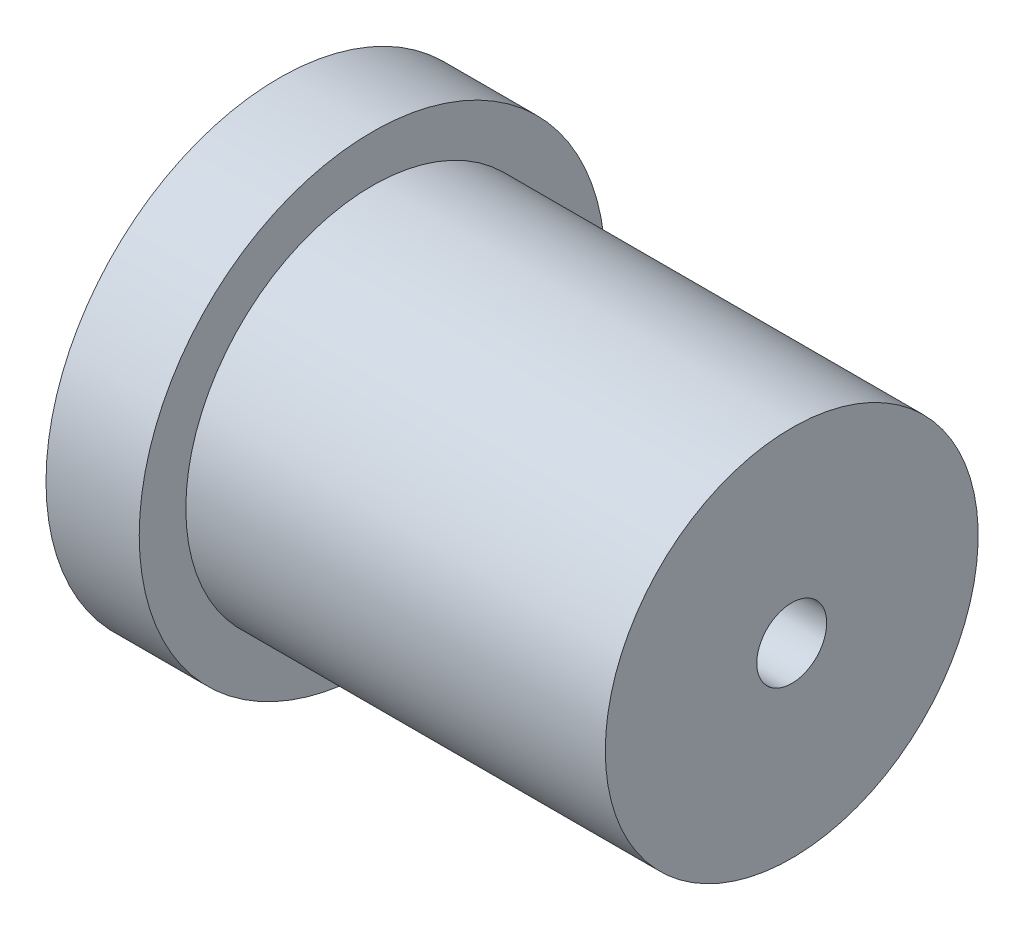
SolidWorks part; units mm, degrees
ref_plane "Front Plane" through (0, 0, 0) normal (0, 0, 1) x (1, 0, 0)
ref_plane "Top Plane" through (0, 0, 0) normal (0, 1, 0) x (1, 0, 0)
ref_plane "Right Plane" through (0, 0, 0) normal (1, 0, 0) x (0, 0, -1)
sketch "Sketch1" plane through (0, 0, 0) normal (0, 0, 1) x (1, 0, 0)
  line L0 (-2.75, 2.5) -> (-1.75, 2.5)
  line L1 (-2.75, 2.5) -> (2.75, 2.5) construction
  line L2 (-2.75, 2.5) -> (-2.75, 0) construction
  line L3 (-2.75, 0) -> (2.75, 0) construction
  line L4 (2.75, 2.5) -> (2.75, 0) construction
  line L5 (-2.75, 0.375) -> (2.75, 0.375)
  line L6 (-2.75, 0.375) -> (-2.75, 2.5)
  line L8 (2.75, 0.375) -> (2.75, 2)
  line L9 (-1.75, 2.5) -> (-1.75, 2)
  line L10 (-1.75, 2) -> (2.75, 2)
  dimension "D1" = 2.5
  dimension "D2" = 5.5
  dimension "D3" = 0.375
  dimension "D4" = 2
  dimension "D5" = 1
revolve "Revolve1" add sketch "Sketch1" angle 360 about L3
